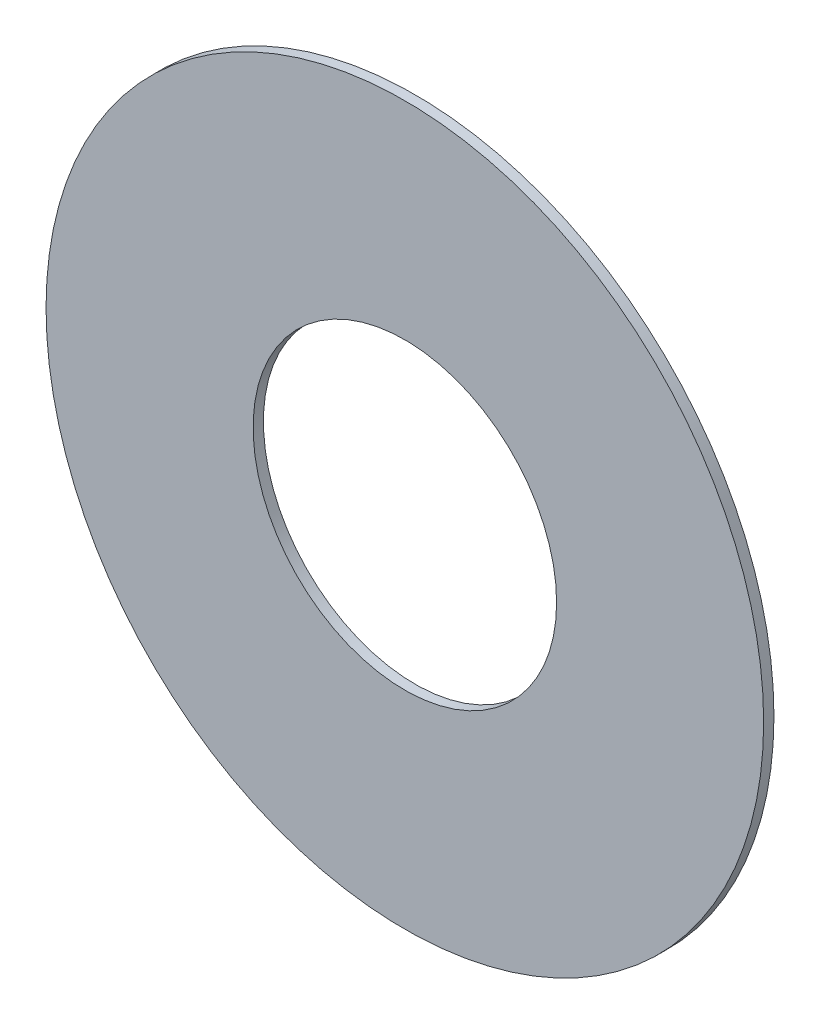
SolidWorks part; units mm, degrees
ref_plane "Спереди" through (0, 0, 0) normal (0, 0, 1) x (1, 0, 0)
ref_plane "Сверху" through (0, 0, 0) normal (0, 1, 0) x (1, 0, 0)
ref_plane "Справа" through (0, 0, 0) normal (1, 0, 0) x (0, 0, -1)
sketch "Эскиз1" plane through (0, 0, 0) normal (0, 0, 1) x (1, 0, 0)
  circle A0 centre (0, 0) radius 69.7538
  circle A1 centre (0, 0) radius 29.5
extrude "Printed_guard" add sketch "Эскиз1" along normal blind 2 from offset 40.5
